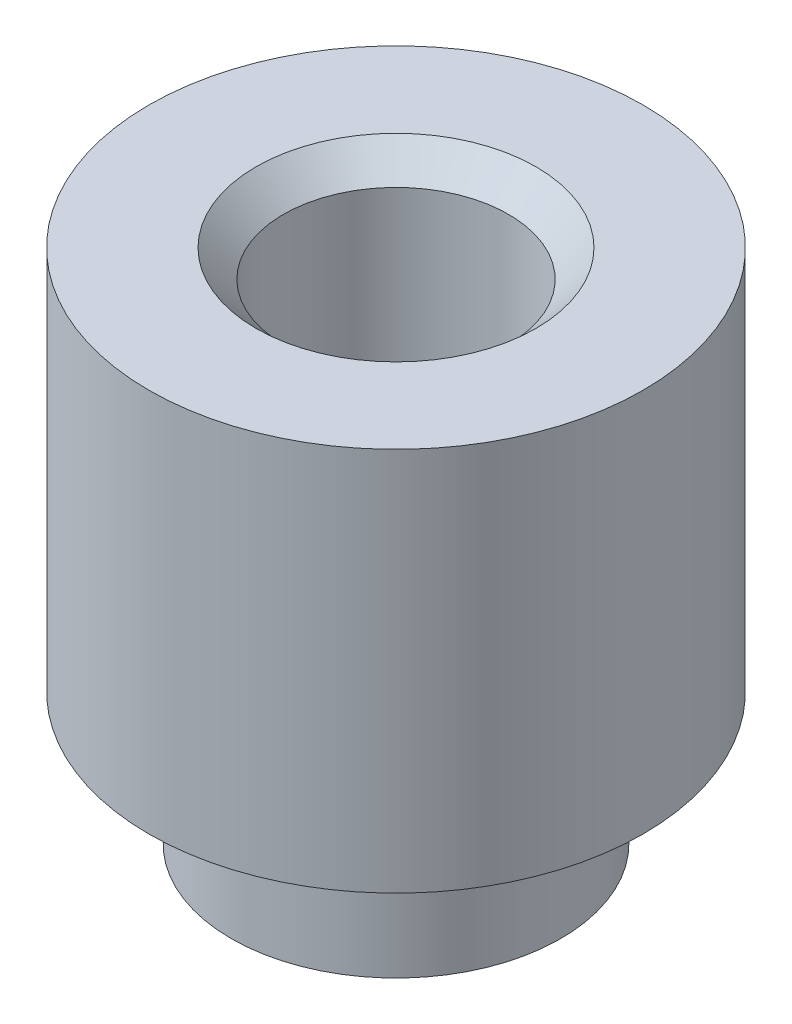
SolidWorks part; units mm, degrees
ref_plane "前视基准面" through (0, 0, 0) normal (0, 0, 1) x (1, 0, 0)
ref_plane "上视基准面" through (0, 0, 0) normal (0, 1, 0) x (1, 0, 0)
ref_plane "右视基准面" through (0, 0, 0) normal (1, 0, 0) x (0, 0, -1)
other "Configuration Table"
sketch "草图1" plane through (0, 0, 0) normal (0, 1, 0) x (1, 0, 0)
  circle A0 centre (0, 0) radius 1.5
  dimension "D1" = 3
extrude "凸台-拉伸1" add sketch "草图1" along normal blind 1.2
sketch "草图2" plane through (0, 1.2, 0) normal (0, 1, 0) x (1, 0, 0)
  circle A0 centre (0, 0) radius 2.25
  dimension "D1" = 4.5
extrude "凸台-拉伸2" add sketch "草图2" along normal blind 3.5
sketch "草图3" plane through (0, 4.7, 0) normal (0, 1, 0) x (1, 0, 0)
  point P0 (0, 0)
hole_wizard "M2.5 螺纹孔1" positions "草图4" profile "草图5" tap size "M2.5" standard "GB" end condition through all
sketch "草图4" plane through (0, 4.7, 0) normal (0, 1, 0) x (1, 0, 0)
  point P0 (0, 0)
sketch "草图5" plane through (0, 4.7, 0) normal (1, 0, 0) x (0, 0, 1)
  line L0 (0, 0) -> (0, 4.7)
  line L1 (0, 4.7) -> (1.025, 4.7)
  line L2 (1.025, 4.7) -> (1.025, 0.25)
  line L3 (1.025, 0.25) -> (1.275, 0)
  line L5 (1.275, 0) -> (0, 0)
  line L6 (-1.025, 0.25) -> (-1.275, 0) construction
  line L11 (0, -6.35) -> (0, 107.95) construction
  dimension "通孔螺纹孔钻头直径" = 2.05
  dimension "通孔螺纹孔钻头深度" = 4.7
  dimension "近端锥形沉头孔直径" = 2.55
  dimension "近端锥形沉头孔角度" = 90
cosmetic thread "孔螺蚊线1"
